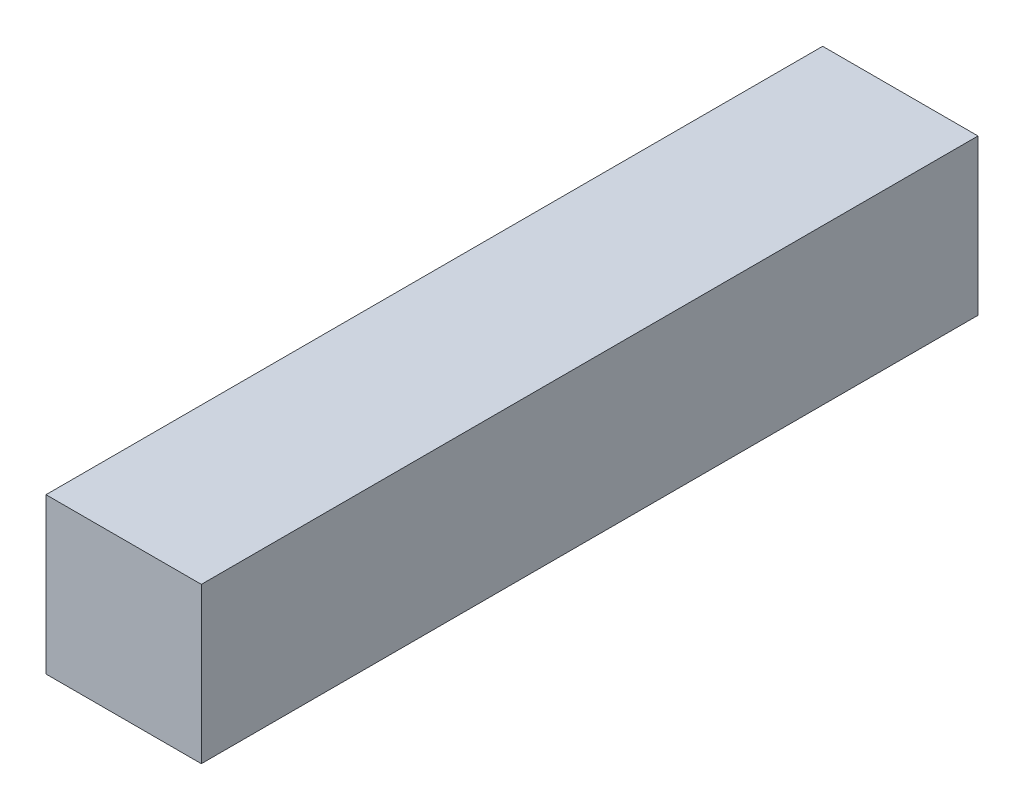
SolidWorks part; units mm, degrees
ref_plane "Front Plane" through (0, 0, 0) normal (0, 0, 1) x (1, 0, 0)
ref_plane "Top Plane" through (0, 0, 0) normal (0, 1, 0) x (1, 0, 0)
ref_plane "Right Plane" through (0, 0, 0) normal (1, 0, 0) x (0, 0, -1)
sketch "Sketch1" plane through (0, 0, 0) normal (0, 0, 1) x (1, 0, 0)
  line L1 (0, 0) -> (3, 0)
  line L2 (0, 0) -> (0, 3)
  line L3 (0, 3) -> (3, 3)
  line L4 (3, 0) -> (3, 3)
  dimension "D1" = 3
  dimension "D2" = 3
extrude "Boss-Extrude1" add sketch "Sketch1" along normal blind 15
